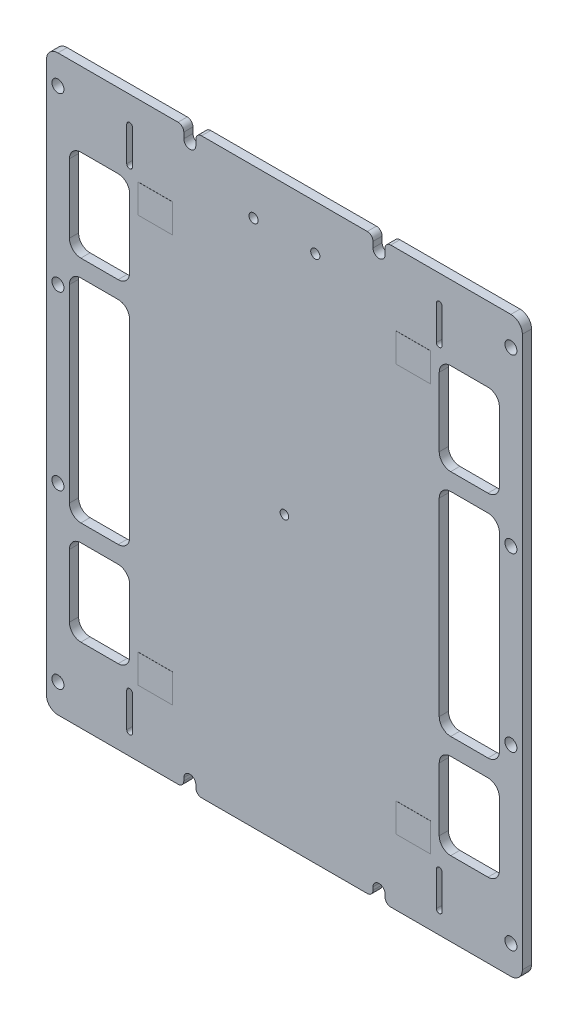
SolidWorks part; units mm, degrees
material "FR4_stuffedProtoboard"
ref_plane "Front Plane" through (0, 0, 0) normal (0, 0, 1) x (1, 0, 0)
ref_plane "Top Plane" through (0, 0, 0) normal (0, 1, 0) x (1, 0, 0)
ref_plane "Right Plane" through (0, 0, 0) normal (1, 0, 0) x (0, 0, -1)
sketch "Sketch1" plane through (0, 0, 0) normal (0, 0, 1) x (1, 0, 0)
  line L1 (-39.5, -50) -> (39.5, -50)
  line L2 (-41.5, -48) -> (-41.5, 48)
  line L3 (-39.5, 50) -> (39.5, 50)
  line L4 (41.5, -48) -> (41.5, 48)
  line L5 (-41.5, -50) -> (41.5, 50) construction
  line L6 (-41.5, 50) -> (41.5, -50) construction
  arc A0 (-39.5, -50) -> (-41.5, -48) centre (-39.5, -48) cw
  arc A1 (39.5, -50) -> (41.5, -48) centre (39.5, -48) ccw
  arc A2 (39.5, 50) -> (41.5, 48) centre (39.5, 48) cw
  arc A3 (-41.5, 48) -> (-39.5, 50) centre (-39.5, 48) cw
  point P0 (0, 0)
  dimension "D3" = 2
  dimension "D1" = 100
  dimension "D2" = 83
extrude "boardOutline" add sketch "Sketch1" along normal blind 1.6
sketch "Sketch2" plane through (0, 0, 1.6) normal (0, 0, 1) x (1, 0, 0)
  line L0 (39.5, 50) -> (-39.5, 50) construction
  line L1 (-41.5, 48) -> (-41.5, -48) construction
  line L2 (-5.385, 42.1) -> (5.385, 42.1) construction
  line L3 (-38, 44.2) -> (-38, 4.2) construction
  line L4 (0, 42.1) -> (0, 50) construction
  circle A0 centre (0, 0) radius 0.75
  circle A1 centre (-38, 44.2) radius 1.05 construction
  circle A2 centre (37.5, 44.2) radius 1.05 construction
  circle A3 centre (37.5, 4.2) radius 1.05 construction
  circle A4 centre (37.5, -35.8) radius 1.05 construction
  circle A5 centre (-38, 4.2) radius 1.05 construction
  circle A6 centre (-38, -35.8) radius 1.05 construction
  circle A7 centre (-5.385, 42.1) radius 0.8
  circle A8 centre (5.385, 42.1) radius 0.8
  dimension "D1" = 1.5
  dimension "D2" = 2.1
  dimension "D9" = 10.77
  dimension "D7" = 1.6
  dimension "D11" = 7.9
  dimension "D3" = 5.8
  dimension "D4" = 3.5
  dimension "D8" = 40
  dimension "D10" = 37.5
  dimension "D5" = 2
  dimension "D6" = 3
extrude "componentHoles" cut sketch "Sketch2" against normal through all
sketch "Sketch4" plane through (0, 0, 1.6) normal (0, 0, 1) x (1, 0, 0)
  line L0 (-27, 39.25) -> (-27, 45.25) construction
  line L1 (-27.5, 39.25) -> (-27.5, 45.25)
  line L2 (-26.5, 39.25) -> (-26.5, 45.25)
  line L3 (39.5, 50) -> (-39.5, 50) construction
  line L4 (-41.5, 48) -> (-41.5, -48) construction
  line L5 (27, 39.25) -> (27, 45.25) construction
  line L6 (26.5, 39.25) -> (26.5, 45.25)
  line L7 (27.5, 39.25) -> (27.5, 45.25)
  line L8 (27, -46.25) -> (27, -40.25) construction
  line L9 (26.5, -46.25) -> (26.5, -40.25)
  line L10 (27.5, -46.25) -> (27.5, -40.25)
  line L11 (-27, -46.25) -> (-27, -40.25) construction
  line L12 (-27.5, -46.25) -> (-27.5, -40.25)
  line L13 (-26.5, -46.25) -> (-26.5, -40.25)
  line L14 (-27, 39.25) -> (27, 39.25) construction
  line L15 (0, 39.25) -> (0, 50) construction
  arc A0 (-27.5, 39.25) -> (-26.5, 39.25) centre (-27, 39.25) ccw
  arc A1 (-26.5, 45.25) -> (-27.5, 45.25) centre (-27, 45.25) ccw
  arc A2 (26.5, 39.25) -> (27.5, 39.25) centre (27, 39.25) ccw
  arc A3 (27.5, 45.25) -> (26.5, 45.25) centre (27, 45.25) ccw
  arc A4 (26.5, -46.25) -> (27.5, -46.25) centre (27, -46.25) ccw
  arc A5 (27.5, -40.25) -> (26.5, -40.25) centre (27, -40.25) ccw
  arc A6 (-27.5, -46.25) -> (-26.5, -46.25) centre (-27, -46.25) ccw
  arc A7 (-26.5, -40.25) -> (-27.5, -40.25) centre (-27, -40.25) ccw
  point P2 (-27, 42.25)
  point P16 (27, 42.25)
  point P23 (27, -43.25)
  point P30 (-27, -43.25)
  dimension "D1" = 4.75
  dimension "D2" = 14
  dimension "D3" = 1
  dimension "D4" = 6
  dimension "D7" = 54
  dimension "D9" = 79.5
  dimension "D5" = 2
  dimension "D6" = 2
extrude "solarCellContactHoles" cut sketch "Sketch4" against normal blind 1.6
sketch "FrameLattice" plane through (0, 0, 0) normal (0, 0, 1) x (1, 0, 0)
  line L4 (-12.5, -19) -> (12.5, -19)
  line L5 (14.5, -17) -> (14.5, 16)
  line L6 (12.5, 18) -> (-12.5, 18)
  line L7 (-14.5, 16) -> (-14.5, -17)
  line L8 (-12.5, -19) -> (12.5, -19)
  line L9 (14.5, -17) -> (14.5, 16)
  line L10 (12.5, 18) -> (-12.5, 18)
  line L11 (-14.5, 16) -> (-14.5, -17)
  line L12 (-12.5, -92) -> (12.5, -92)
  line L13 (14.5, -90) -> (14.5, -69)
  line L14 (12.5, -67) -> (-12.5, -67)
  line L15 (-14.5, -69) -> (-14.5, -90)
  line L16 (-12.5, -92) -> (12.5, -92)
  line L17 (14.5, -90) -> (14.5, -69)
  line L18 (12.5, -67) -> (-12.5, -67)
  line L19 (-14.5, -69) -> (-14.5, -90)
  line L20 (-35.5, -132) -> (-19.5, -132)
  line L21 (-17.5, -130) -> (-17.5, -97)
  line L22 (-19.5, -95) -> (-35.5, -95)
  line L23 (-37.5, -97) -> (-37.5, -130)
  line L24 (-35.5, -132) -> (-19.5, -132)
  line L25 (-17.5, -130) -> (-17.5, -97)
  line L26 (-19.5, -95) -> (-35.5, -95)
  line L27 (-37.5, -97) -> (-37.5, -130)
  line L28 (19.5, -160) -> (35.5, -160)
  line L29 (37.5, -158) -> (37.5, -137)
  line L30 (35.5, -135) -> (19.5, -135)
  line L31 (17.5, -137) -> (17.5, -158)
  line L32 (19.5, -160) -> (35.5, -160)
  line L33 (37.5, -158) -> (37.5, -137)
  line L34 (35.5, -135) -> (19.5, -135)
  line L35 (17.5, -137) -> (17.5, -158)
  line L36 (19.5, -92) -> (35.5, -92)
  line L37 (37.5, -90) -> (37.5, -69)
  line L38 (35.5, -67) -> (19.5, -67)
  line L39 (17.5, -69) -> (17.5, -90)
  line L40 (19.5, -92) -> (35.5, -92)
  line L41 (37.5, -90) -> (37.5, -69)
  line L42 (35.5, -67) -> (19.5, -67)
  line L43 (17.5, -69) -> (17.5, -90)
  line L44 (-35.5, -92) -> (-19.5, -92)
  line L45 (-17.5, -90) -> (-17.5, -69)
  line L46 (-19.5, -67) -> (-35.5, -67)
  line L47 (-37.5, -69) -> (-37.5, -90)
  line L48 (-35.5, -92) -> (-19.5, -92)
  line L49 (-17.5, -90) -> (-17.5, -69)
  line L50 (-19.5, -67) -> (-35.5, -67)
  line L51 (-37.5, -69) -> (-37.5, -90)
  line L52 (19.5, -132) -> (35.5, -132)
  line L53 (37.5, -130) -> (37.5, -97)
  line L54 (35.5, -95) -> (19.5, -95)
  line L55 (17.5, -97) -> (17.5, -130)
  line L56 (19.5, -132) -> (35.5, -132)
  line L57 (37.5, -130) -> (37.5, -97)
  line L58 (35.5, -95) -> (19.5, -95)
  line L59 (17.5, -97) -> (17.5, -130)
  line L60 (-12.5, -160) -> (12.5, -160)
  line L61 (14.5, -158) -> (14.5, -137)
  line L62 (12.5, -135) -> (-12.5, -135)
  line L63 (-14.5, -137) -> (-14.5, -158)
  line L64 (-12.5, -160) -> (12.5, -160)
  line L65 (14.5, -158) -> (14.5, -137)
  line L66 (12.5, -135) -> (-12.5, -135)
  line L67 (-14.5, -137) -> (-14.5, -158)
  line L68 (-26.75, -62) -> (-26.75, -52)
  line L69 (-28.75, -50) -> (-35, -50)
  line L70 (-37, -52) -> (-37, -62)
  line L71 (-35, -64) -> (-28.75, -64)
  line L72 (-26.75, -62) -> (-26.75, -52)
  line L73 (-28.75, -50) -> (-35, -50)
  line L74 (-37, -52) -> (-37, -62)
  line L75 (-35, -64) -> (-28.75, -64)
  line L76 (-35.5, -160) -> (-19.5, -160)
  line L77 (-17.5, -158) -> (-17.5, -137)
  line L78 (-19.5, -135) -> (-35.5, -135)
  line L79 (-37.5, -137) -> (-37.5, -158)
  line L80 (-35.5, -160) -> (-19.5, -160)
  line L81 (-17.5, -158) -> (-17.5, -137)
  line L82 (-19.5, -135) -> (-35.5, -135)
  line L83 (-37.5, -137) -> (-37.5, -158)
  line L84 (-12.5, -132) -> (12.5, -132)
  line L85 (14.5, -130) -> (14.5, -97)
  line L86 (12.5, -95) -> (-12.5, -95)
  line L87 (-14.5, -97) -> (-14.5, -130)
  line L88 (-12.5, -132) -> (12.5, -132)
  line L89 (14.5, -130) -> (14.5, -97)
  line L90 (12.5, -95) -> (-12.5, -95)
  line L91 (-14.5, -97) -> (-14.5, -130)
  line L92 (-35.5, -19) -> (-19.5, -19)
  line L93 (-17.5, -17) -> (-17.5, 16)
  line L94 (-19.5, 18) -> (-35.5, 18)
  line L95 (-37.5, 16) -> (-37.5, -17)
  line L96 (-35.5, -19) -> (-19.5, -19)
  line L97 (-17.5, -17) -> (-17.5, 16)
  line L98 (-19.5, 18) -> (-35.5, 18)
  line L99 (-37.5, 16) -> (-37.5, -17)
  line L100 (19.5, -47) -> (35.5, -47)
  line L101 (37.5, -45) -> (37.5, -24)
  line L102 (35.5, -22) -> (19.5, -22)
  line L103 (17.5, -24) -> (17.5, -45)
  line L104 (19.5, -47) -> (35.5, -47)
  line L105 (37.5, -45) -> (37.5, -24)
  line L106 (35.5, -22) -> (19.5, -22)
  line L107 (17.5, -24) -> (17.5, -45)
  line L108 (-12.5, -47) -> (12.5, -47)
  line L109 (14.5, -45) -> (14.5, -24)
  line L110 (12.5, -22) -> (-12.5, -22)
  line L111 (-14.5, -24) -> (-14.5, -45)
  line L112 (-12.5, -47) -> (12.5, -47)
  line L113 (14.5, -45) -> (14.5, -24)
  line L114 (12.5, -22) -> (-12.5, -22)
  line L115 (-14.5, -24) -> (-14.5, -45)
  line L116 (-35.5, -47) -> (-19.5, -47)
  line L117 (-17.5, -45) -> (-17.5, -24)
  line L118 (-19.5, -22) -> (-35.5, -22)
  line L119 (-37.5, -24) -> (-37.5, -45)
  line L120 (-35.5, -47) -> (-19.5, -47)
  line L121 (-17.5, -45) -> (-17.5, -24)
  line L122 (-19.5, -22) -> (-35.5, -22)
  line L123 (-37.5, -24) -> (-37.5, -45)
  line L124 (19.5, -19) -> (35.5, -19)
  line L125 (37.5, -17) -> (37.5, 16)
  line L126 (35.5, 18) -> (19.5, 18)
  line L127 (17.5, 16) -> (17.5, -17)
  line L128 (19.5, -19) -> (35.5, -19)
  line L129 (37.5, -17) -> (37.5, 16)
  line L130 (35.5, 18) -> (19.5, 18)
  line L131 (17.5, 16) -> (17.5, -17)
  line L132 (-35.5, 21) -> (-19.5, 21)
  line L133 (-17.5, 23) -> (-17.5, 44)
  line L134 (-19.5, 46) -> (-35.5, 46)
  line L135 (-37.5, 44) -> (-37.5, 23)
  line L136 (-35.5, 21) -> (-19.5, 21)
  line L137 (-17.5, 23) -> (-17.5, 44)
  line L138 (-19.5, 46) -> (-35.5, 46)
  line L139 (-37.5, 44) -> (-37.5, 23)
  line L140 (-12.5, 21) -> (12.5, 21)
  line L141 (14.5, 23) -> (14.5, 44)
  line L142 (12.5, 46) -> (-12.5, 46)
  line L143 (-14.5, 44) -> (-14.5, 23)
  line L144 (-12.5, 21) -> (12.5, 21)
  line L145 (14.5, 23) -> (14.5, 44)
  line L146 (12.5, 46) -> (-12.5, 46)
  line L147 (-14.5, 44) -> (-14.5, 23)
  line L148 (19.5, 21) -> (35.5, 21)
  line L149 (37.5, 23) -> (37.5, 44)
  line L150 (35.5, 46) -> (19.5, 46)
  line L151 (17.5, 44) -> (17.5, 23)
  line L152 (19.5, 21) -> (35.5, 21)
  line L153 (37.5, 23) -> (37.5, 44)
  line L154 (35.5, 46) -> (19.5, 46)
  line L155 (17.5, 44) -> (17.5, 23)
  line L156 (-3.5, -62) -> (-3.5, -52)
  line L157 (-5.5, -50) -> (-13, -50)
  line L158 (-15, -52) -> (-15, -62)
  line L159 (-13, -64) -> (-5.5, -64)
  line L160 (-3.5, -62) -> (-3.5, -52)
  line L161 (-5.5, -50) -> (-13, -50)
  line L162 (-15, -52) -> (-15, -62)
  line L163 (-13, -64) -> (-5.5, -64)
  line L164 (28.75, -64) -> (35, -64)
  line L165 (37, -62) -> (37, -52)
  line L166 (35, -50) -> (28.75, -50)
  line L167 (26.75, -52) -> (26.75, -62)
  line L168 (28.75, -64) -> (35, -64)
  line L169 (37, -62) -> (37, -52)
  line L170 (35, -50) -> (28.75, -50)
  line L171 (26.75, -52) -> (26.75, -62)
  line L172 (5.5, -64) -> (13, -64)
  line L173 (15, -62) -> (15, -52)
  line L174 (13, -50) -> (5.5, -50)
  line L175 (3.5, -52) -> (3.5, -62)
  line L176 (5.5, -64) -> (13, -64)
  line L177 (15, -62) -> (15, -52)
  line L178 (13, -50) -> (5.5, -50)
  line L179 (3.5, -52) -> (3.5, -62)
  circle A2 centre (-16.5, 48) radius 0.8
  circle A3 centre (-16.5, 48) radius 0.8
  circle A4 centre (-16.5, -162) radius 0.8
  arc A5 (12.5, -19) -> (14.5, -17) centre (12.5, -17) ccw
  arc A6 (14.5, 16) -> (12.5, 18) centre (12.5, 16) ccw
  arc A7 (-12.5, 18) -> (-14.5, 16) centre (-12.5, 16) ccw
  arc A8 (-14.5, -17) -> (-12.5, -19) centre (-12.5, -17) ccw
  arc A9 (12.5, -19) -> (14.5, -17) centre (12.5, -17) ccw
  arc A10 (14.5, 16) -> (12.5, 18) centre (12.5, 16) ccw
  arc A11 (-12.5, 18) -> (-14.5, 16) centre (-12.5, 16) ccw
  arc A12 (-14.5, -17) -> (-12.5, -19) centre (-12.5, -17) ccw
  arc A13 (12.5, -92) -> (14.5, -90) centre (12.5, -90) ccw
  arc A14 (14.5, -69) -> (12.5, -67) centre (12.5, -69) ccw
  arc A15 (-12.5, -67) -> (-14.5, -69) centre (-12.5, -69) ccw
  arc A16 (-14.5, -90) -> (-12.5, -92) centre (-12.5, -90) ccw
  arc A17 (12.5, -92) -> (14.5, -90) centre (12.5, -90) ccw
  arc A18 (14.5, -69) -> (12.5, -67) centre (12.5, -69) ccw
  arc A19 (-12.5, -67) -> (-14.5, -69) centre (-12.5, -69) ccw
  arc A20 (-14.5, -90) -> (-12.5, -92) centre (-12.5, -90) ccw
  arc A21 (-19.5, -132) -> (-17.5, -130) centre (-19.5, -130) ccw
  arc A22 (-17.5, -97) -> (-19.5, -95) centre (-19.5, -97) ccw
  arc A23 (-35.5, -95) -> (-37.5, -97) centre (-35.5, -97) ccw
  arc A24 (-37.5, -130) -> (-35.5, -132) centre (-35.5, -130) ccw
  arc A25 (-19.5, -132) -> (-17.5, -130) centre (-19.5, -130) ccw
  arc A26 (-17.5, -97) -> (-19.5, -95) centre (-19.5, -97) ccw
  arc A27 (-35.5, -95) -> (-37.5, -97) centre (-35.5, -97) ccw
  arc A28 (-37.5, -130) -> (-35.5, -132) centre (-35.5, -130) ccw
  arc A29 (35.5, -160) -> (37.5, -158) centre (35.5, -158) ccw
  arc A30 (37.5, -137) -> (35.5, -135) centre (35.5, -137) ccw
  arc A31 (19.5, -135) -> (17.5, -137) centre (19.5, -137) ccw
  arc A32 (17.5, -158) -> (19.5, -160) centre (19.5, -158) ccw
  arc A33 (35.5, -160) -> (37.5, -158) centre (35.5, -158) ccw
  arc A34 (37.5, -137) -> (35.5, -135) centre (35.5, -137) ccw
  arc A35 (19.5, -135) -> (17.5, -137) centre (19.5, -137) ccw
  arc A36 (17.5, -158) -> (19.5, -160) centre (19.5, -158) ccw
  arc A37 (35.5, -92) -> (37.5, -90) centre (35.5, -90) ccw
  arc A38 (37.5, -69) -> (35.5, -67) centre (35.5, -69) ccw
  arc A39 (19.5, -67) -> (17.5, -69) centre (19.5, -69) ccw
  arc A40 (17.5, -90) -> (19.5, -92) centre (19.5, -90) ccw
  arc A41 (35.5, -92) -> (37.5, -90) centre (35.5, -90) ccw
  arc A42 (37.5, -69) -> (35.5, -67) centre (35.5, -69) ccw
  arc A43 (19.5, -67) -> (17.5, -69) centre (19.5, -69) ccw
  arc A44 (17.5, -90) -> (19.5, -92) centre (19.5, -90) ccw
  arc A45 (-19.5, -92) -> (-17.5, -90) centre (-19.5, -90) ccw
  arc A46 (-17.5, -69) -> (-19.5, -67) centre (-19.5, -69) ccw
  arc A47 (-35.5, -67) -> (-37.5, -69) centre (-35.5, -69) ccw
  arc A48 (-37.5, -90) -> (-35.5, -92) centre (-35.5, -90) ccw
  arc A49 (-19.5, -92) -> (-17.5, -90) centre (-19.5, -90) ccw
  arc A50 (-17.5, -69) -> (-19.5, -67) centre (-19.5, -69) ccw
  arc A51 (-35.5, -67) -> (-37.5, -69) centre (-35.5, -69) ccw
  arc A52 (-37.5, -90) -> (-35.5, -92) centre (-35.5, -90) ccw
  arc A53 (35.5, -132) -> (37.5, -130) centre (35.5, -130) ccw
  arc A54 (37.5, -97) -> (35.5, -95) centre (35.5, -97) ccw
  arc A55 (19.5, -95) -> (17.5, -97) centre (19.5, -97) ccw
  arc A56 (17.5, -130) -> (19.5, -132) centre (19.5, -130) ccw
  arc A57 (35.5, -132) -> (37.5, -130) centre (35.5, -130) ccw
  arc A58 (37.5, -97) -> (35.5, -95) centre (35.5, -97) ccw
  arc A59 (19.5, -95) -> (17.5, -97) centre (19.5, -97) ccw
  arc A60 (17.5, -130) -> (19.5, -132) centre (19.5, -130) ccw
  arc A61 (12.5, -160) -> (14.5, -158) centre (12.5, -158) ccw
  arc A62 (14.5, -137) -> (12.5, -135) centre (12.5, -137) ccw
  arc A63 (-12.5, -135) -> (-14.5, -137) centre (-12.5, -137) ccw
  arc A64 (-14.5, -158) -> (-12.5, -160) centre (-12.5, -158) ccw
  arc A65 (12.5, -160) -> (14.5, -158) centre (12.5, -158) ccw
  arc A66 (14.5, -137) -> (12.5, -135) centre (12.5, -137) ccw
  arc A67 (-12.5, -135) -> (-14.5, -137) centre (-12.5, -137) ccw
  arc A68 (-14.5, -158) -> (-12.5, -160) centre (-12.5, -158) ccw
  circle A69 centre (-16.5, -162) radius 0.8
  circle A70 centre (16.5, -162) radius 0.8
  circle A71 centre (16.5, -162) radius 0.8
  circle A72 centre (-16.5, -65.5) radius 0.8
  circle A73 centre (-16.5, -65.5) radius 0.8
  circle A74 centre (16.5, -65.5) radius 0.8
  circle A75 centre (16.5, -65.5) radius 0.8
  circle A76 centre (-39.5, -129) radius 0.8
  circle A77 centre (-39.5, -129) radius 0.8
  circle A78 centre (39.5, -159) radius 0.8
  circle A79 centre (39.5, -159) radius 0.8
  circle A80 centre (-39.5, -159) radius 0.8
  circle A81 centre (-39.5, -159) radius 0.8
  circle A82 centre (39.5, -129) radius 0.8
  circle A83 centre (39.5, -129) radius 0.8
  circle A84 centre (39.5, -99) radius 0.8
  circle A85 centre (39.5, -99) radius 0.8
  circle A86 centre (-39.5, -99) radius 0.8
  circle A87 centre (-39.5, -99) radius 0.8
  circle A88 centre (-39.5, -69) radius 0.8
  circle A89 centre (-39.5, -69) radius 0.8
  circle A90 centre (39.5, -69) radius 0.8
  circle A91 centre (39.5, -69) radius 0.8
  circle A92 centre (39.5, -15) radius 0.8
  circle A93 centre (39.5, -15) radius 0.8
  circle A94 centre (39.5, 15) radius 0.8
  arc A95 (-26.75, -52) -> (-28.75, -50) centre (-28.75, -52) ccw
  arc A96 (-35, -50) -> (-37, -52) centre (-35, -52) ccw
  arc A97 (-37, -62) -> (-35, -64) centre (-35, -62) ccw
  arc A98 (-28.75, -64) -> (-26.75, -62) centre (-28.75, -62) ccw
  arc A99 (-26.75, -52) -> (-28.75, -50) centre (-28.75, -52) ccw
  arc A100 (-35, -50) -> (-37, -52) centre (-35, -52) ccw
  arc A101 (-37, -62) -> (-35, -64) centre (-35, -62) ccw
  arc A102 (-28.75, -64) -> (-26.75, -62) centre (-28.75, -62) ccw
  arc A103 (-19.5, -160) -> (-17.5, -158) centre (-19.5, -158) ccw
  arc A104 (-17.5, -137) -> (-19.5, -135) centre (-19.5, -137) ccw
  arc A105 (-35.5, -135) -> (-37.5, -137) centre (-35.5, -137) ccw
  arc A106 (-37.5, -158) -> (-35.5, -160) centre (-35.5, -158) ccw
  arc A107 (-19.5, -160) -> (-17.5, -158) centre (-19.5, -158) ccw
  arc A108 (-17.5, -137) -> (-19.5, -135) centre (-19.5, -137) ccw
  arc A109 (-35.5, -135) -> (-37.5, -137) centre (-35.5, -137) ccw
  arc A110 (-37.5, -158) -> (-35.5, -160) centre (-35.5, -158) ccw
  arc A111 (12.5, -132) -> (14.5, -130) centre (12.5, -130) ccw
  arc A112 (14.5, -97) -> (12.5, -95) centre (12.5, -97) ccw
  arc A113 (-12.5, -95) -> (-14.5, -97) centre (-12.5, -97) ccw
  arc A114 (-14.5, -130) -> (-12.5, -132) centre (-12.5, -130) ccw
  arc A115 (12.5, -132) -> (14.5, -130) centre (12.5, -130) ccw
  arc A116 (14.5, -97) -> (12.5, -95) centre (12.5, -97) ccw
  arc A117 (-12.5, -95) -> (-14.5, -97) centre (-12.5, -97) ccw
  arc A118 (-14.5, -130) -> (-12.5, -132) centre (-12.5, -130) ccw
  arc A119 (-19.5, -19) -> (-17.5, -17) centre (-19.5, -17) ccw
  arc A120 (-17.5, 16) -> (-19.5, 18) centre (-19.5, 16) ccw
  arc A121 (-35.5, 18) -> (-37.5, 16) centre (-35.5, 16) ccw
  arc A122 (-37.5, -17) -> (-35.5, -19) centre (-35.5, -17) ccw
  arc A123 (-19.5, -19) -> (-17.5, -17) centre (-19.5, -17) ccw
  arc A124 (-17.5, 16) -> (-19.5, 18) centre (-19.5, 16) ccw
  arc A125 (-35.5, 18) -> (-37.5, 16) centre (-35.5, 16) ccw
  arc A126 (-37.5, -17) -> (-35.5, -19) centre (-35.5, -17) ccw
  arc A127 (35.5, -47) -> (37.5, -45) centre (35.5, -45) ccw
  arc A128 (37.5, -24) -> (35.5, -22) centre (35.5, -24) ccw
  arc A129 (19.5, -22) -> (17.5, -24) centre (19.5, -24) ccw
  arc A130 (17.5, -45) -> (19.5, -47) centre (19.5, -45) ccw
  arc A131 (35.5, -47) -> (37.5, -45) centre (35.5, -45) ccw
  arc A132 (37.5, -24) -> (35.5, -22) centre (35.5, -24) ccw
  arc A133 (19.5, -22) -> (17.5, -24) centre (19.5, -24) ccw
  arc A134 (17.5, -45) -> (19.5, -47) centre (19.5, -45) ccw
  arc A135 (12.5, -47) -> (14.5, -45) centre (12.5, -45) ccw
  arc A136 (14.5, -24) -> (12.5, -22) centre (12.5, -24) ccw
  arc A137 (-12.5, -22) -> (-14.5, -24) centre (-12.5, -24) ccw
  arc A138 (-14.5, -45) -> (-12.5, -47) centre (-12.5, -45) ccw
  arc A139 (12.5, -47) -> (14.5, -45) centre (12.5, -45) ccw
  arc A140 (14.5, -24) -> (12.5, -22) centre (12.5, -24) ccw
  arc A141 (-12.5, -22) -> (-14.5, -24) centre (-12.5, -24) ccw
  arc A142 (-14.5, -45) -> (-12.5, -47) centre (-12.5, -45) ccw
  arc A143 (-19.5, -47) -> (-17.5, -45) centre (-19.5, -45) ccw
  arc A144 (-17.5, -24) -> (-19.5, -22) centre (-19.5, -24) ccw
  arc A145 (-35.5, -22) -> (-37.5, -24) centre (-35.5, -24) ccw
  arc A146 (-37.5, -45) -> (-35.5, -47) centre (-35.5, -45) ccw
  arc A147 (-19.5, -47) -> (-17.5, -45) centre (-19.5, -45) ccw
  arc A148 (-17.5, -24) -> (-19.5, -22) centre (-19.5, -24) ccw
  arc A149 (-35.5, -22) -> (-37.5, -24) centre (-35.5, -24) ccw
  arc A150 (-37.5, -45) -> (-35.5, -47) centre (-35.5, -45) ccw
  arc A151 (35.5, -19) -> (37.5, -17) centre (35.5, -17) ccw
  arc A152 (37.5, 16) -> (35.5, 18) centre (35.5, 16) ccw
  arc A153 (19.5, 18) -> (17.5, 16) centre (19.5, 16) ccw
  arc A154 (17.5, -17) -> (19.5, -19) centre (19.5, -17) ccw
  arc A155 (35.5, -19) -> (37.5, -17) centre (35.5, -17) ccw
  arc A156 (37.5, 16) -> (35.5, 18) centre (35.5, 16) ccw
  arc A157 (19.5, 18) -> (17.5, 16) centre (19.5, 16) ccw
  arc A158 (17.5, -17) -> (19.5, -19) centre (19.5, -17) ccw
  arc A159 (-19.5, 21) -> (-17.5, 23) centre (-19.5, 23) ccw
  arc A160 (-17.5, 44) -> (-19.5, 46) centre (-19.5, 44) ccw
  arc A161 (-35.5, 46) -> (-37.5, 44) centre (-35.5, 44) ccw
  arc A162 (-37.5, 23) -> (-35.5, 21) centre (-35.5, 23) ccw
  arc A163 (-19.5, 21) -> (-17.5, 23) centre (-19.5, 23) ccw
  arc A164 (-17.5, 44) -> (-19.5, 46) centre (-19.5, 44) ccw
  arc A165 (-35.5, 46) -> (-37.5, 44) centre (-35.5, 44) ccw
  arc A166 (-37.5, 23) -> (-35.5, 21) centre (-35.5, 23) ccw
  arc A167 (12.5, 21) -> (14.5, 23) centre (12.5, 23) ccw
  arc A168 (14.5, 44) -> (12.5, 46) centre (12.5, 44) ccw
  arc A169 (-12.5, 46) -> (-14.5, 44) centre (-12.5, 44) ccw
  arc A170 (-14.5, 23) -> (-12.5, 21) centre (-12.5, 23) ccw
  arc A171 (12.5, 21) -> (14.5, 23) centre (12.5, 23) ccw
  arc A172 (14.5, 44) -> (12.5, 46) centre (12.5, 44) ccw
  arc A173 (-12.5, 46) -> (-14.5, 44) centre (-12.5, 44) ccw
  arc A174 (-14.5, 23) -> (-12.5, 21) centre (-12.5, 23) ccw
  arc A175 (35.5, 21) -> (37.5, 23) centre (35.5, 23) ccw
  arc A176 (37.5, 44) -> (35.5, 46) centre (35.5, 44) ccw
  arc A177 (19.5, 46) -> (17.5, 44) centre (19.5, 44) ccw
  arc A178 (17.5, 23) -> (19.5, 21) centre (19.5, 23) ccw
  arc A179 (35.5, 21) -> (37.5, 23) centre (35.5, 23) ccw
  arc A180 (37.5, 44) -> (35.5, 46) centre (35.5, 44) ccw
  arc A181 (19.5, 46) -> (17.5, 44) centre (19.5, 44) ccw
  arc A182 (17.5, 23) -> (19.5, 21) centre (19.5, 23) ccw
  circle A183 centre (39.5, 15) radius 0.8
  circle A184 centre (-39.5, 45) radius 0.8
  circle A185 centre (-39.5, 45) radius 0.8
  circle A186 centre (39.5, 45) radius 0.8
  circle A187 centre (39.5, 45) radius 0.8
  circle A188 centre (-39.5, 15) radius 0.8
  circle A189 centre (-39.5, 15) radius 0.8
  circle A190 centre (16.5, -48.5) radius 0.8
  circle A191 centre (16.5, -48.5) radius 0.8
  circle A192 centre (-16.5, -48.5) radius 0.8
  circle A193 centre (-16.5, -48.5) radius 0.8
  circle A194 centre (16.5, 48) radius 0.8
  circle A195 centre (16.5, 48) radius 0.8
  circle A196 centre (-39.5, -15) radius 0.8
  circle A197 centre (-39.5, -15) radius 0.8
  circle A198 centre (-22, -61) radius 2.75
  circle A199 centre (-22, -61) radius 2.75
  circle A200 centre (-22, -53) radius 2.75
  circle A201 centre (-22, -53) radius 2.75
  circle A202 centre (22, -53) radius 2.75
  circle A203 centre (22, -53) radius 2.75
  circle A204 centre (22, -61) radius 2.75
  arc A205 (-3.5, -52) -> (-5.5, -50) centre (-5.5, -52) ccw
  arc A206 (-13, -50) -> (-15, -52) centre (-13, -52) ccw
  arc A207 (-15, -62) -> (-13, -64) centre (-13, -62) ccw
  arc A208 (-5.5, -64) -> (-3.5, -62) centre (-5.5, -62) ccw
  arc A209 (-3.5, -52) -> (-5.5, -50) centre (-5.5, -52) ccw
  arc A210 (-13, -50) -> (-15, -52) centre (-13, -52) ccw
  arc A211 (-15, -62) -> (-13, -64) centre (-13, -62) ccw
  arc A212 (-5.5, -64) -> (-3.5, -62) centre (-5.5, -62) ccw
  circle A213 centre (22, -61) radius 2.75
  circle A214 centre (0, -57) radius 2.75
  circle A215 centre (0, -57) radius 2.75
  circle A216 centre (39.5, -45) radius 0.8
  circle A217 centre (39.5, -45) radius 0.8
  circle A218 centre (-39.5, -45) radius 0.8
  arc A219 (35, -64) -> (37, -62) centre (35, -62) ccw
  arc A220 (37, -52) -> (35, -50) centre (35, -52) ccw
  arc A221 (28.75, -50) -> (26.75, -52) centre (28.75, -52) ccw
  arc A222 (26.75, -62) -> (28.75, -64) centre (28.75, -62) ccw
  arc A223 (35, -64) -> (37, -62) centre (35, -62) ccw
  arc A224 (37, -52) -> (35, -50) centre (35, -52) ccw
  arc A225 (28.75, -50) -> (26.75, -52) centre (28.75, -52) ccw
  arc A226 (26.75, -62) -> (28.75, -64) centre (28.75, -62) ccw
  arc A227 (13, -64) -> (15, -62) centre (13, -62) ccw
  arc A228 (15, -52) -> (13, -50) centre (13, -52) ccw
  arc A229 (5.5, -50) -> (3.5, -52) centre (5.5, -52) ccw
  arc A230 (3.5, -62) -> (5.5, -64) centre (5.5, -62) ccw
  arc A231 (13, -64) -> (15, -62) centre (13, -62) ccw
  arc A232 (15, -52) -> (13, -50) centre (13, -52) ccw
  arc A233 (5.5, -50) -> (3.5, -52) centre (5.5, -52) ccw
  arc A234 (3.5, -62) -> (5.5, -64) centre (5.5, -62) ccw
  circle A235 centre (-39.5, -45) radius 0.8
  dimension "D1" = 0
  dimension "D2" = 0
  dimension "D3" = 0
  dimension "D4" = 0
  dimension "D5" = 0
  dimension "D6" = 0
  dimension "D7" = 0
  dimension "D8" = 0
  dimension "D9" = 0
  dimension "D10" = 0
  dimension "D11" = 0
  dimension "D12" = 0
  dimension "D13" = 0
  dimension "D14" = 0
  dimension "D15" = 0
  dimension "D16" = 0
  dimension "D17" = 0
  dimension "D18" = 0
  dimension "D19" = 0
  dimension "D20" = 0
  dimension "D21" = 0
  dimension "D22" = 0
  dimension "D23" = 0
  dimension "D24" = 0
  dimension "D25" = 0
  dimension "D26" = 0
  dimension "D27" = 0
  dimension "D28" = 0
  dimension "D29" = 0
  dimension "D30" = 0
  dimension "D31" = 0
  dimension "D32" = 0
  dimension "D33" = 0
  dimension "D34" = 0
  dimension "D35" = 0
  dimension "D36" = 0
  dimension "D37" = 0
  dimension "D38" = 0
  dimension "D39" = 0
  dimension "D40" = 0
  dimension "D41" = 0
  dimension "D42" = 0
  dimension "D43" = 0
  dimension "D44" = 0
  dimension "D45" = 0
  dimension "D46" = 0
  dimension "D47" = 0
  dimension "D48" = 0
  dimension "D49" = 0
  dimension "D50" = 0
  dimension "D51" = 0
sketch "Sketch3" plane through (0, 0, 1.6) normal (0, 0, 1) x (1, 0, 0)
  line L0 (-35.5, -19) -> (-19.5, -19) construction
  line L1 (-35.5, 37) -> (-29, 37)
  line L2 (-37.5, 35) -> (-37.5, 23)
  line L3 (-35.5, 21) -> (-29, 21)
  line L4 (-27, 35) -> (-27, 23)
  line L6 (-29, -22) -> (-35.5, -22)
  line L7 (-37.5, 16) -> (-37.5, -17) construction
  line L8 (-19.5, -22) -> (-35.5, -22) construction
  line L9 (0, 50) -> (0, -50) construction
  line L10 (39.5, 50) -> (-39.5, 50) construction
  line L11 (-39.5, -50) -> (39.5, -50) construction
  line L12 (-27, -24) -> (-27, -35)
  line L13 (-29, -37) -> (-35.5, -37)
  line L14 (-37.5, -24) -> (-37.5, -35)
  line L15 (-19.5, 18) -> (-35.5, 18) construction
  line L16 (-35.5, 21) -> (-19.5, 21) construction
  line L19 (-29, -19) -> (-35.5, -19)
  line L25 (-27, -17) -> (-27, 16)
  line L26 (-29, 18) -> (-35.5, 18)
  line L27 (-37.5, -17) -> (-37.5, 16)
  arc A0 (-37.5, 23) -> (-35.5, 21) centre (-35.5, 23) ccw
  arc A1 (-29, 21) -> (-27, 23) centre (-29, 23) ccw
  arc A2 (-29, 37) -> (-27, 35) centre (-29, 35) cw
  arc A3 (-35.5, 37) -> (-37.5, 35) centre (-35.5, 35) ccw
  arc A4 (-29, -19) -> (-27, -17) centre (-29, -17) ccw
  arc A5 (-27, -35) -> (-29, -37) centre (-29, -35) cw
  arc A6 (-35.5, -37) -> (-37.5, -35) centre (-35.5, -35) cw
  arc A7 (-35.5, -22) -> (-37.5, -24) centre (-35.5, -24) ccw
  arc A8 (-29, -22) -> (-27, -24) centre (-29, -24) cw
  arc A9 (-37.5, 23) -> (-35.5, 21) centre (-35.5, 23) ccw construction
  arc A17 (-35.5, -19) -> (-37.5, -17) centre (-35.5, -17) cw
  arc A18 (-35.5, 18) -> (-37.5, 16) centre (-35.5, 16) ccw
  arc A19 (-27, 16) -> (-29, 18) centre (-29, 16) ccw
  point P12 (-27, 21)
  point P15 (-27, 37)
  point P18 (-37.5, 37)
  dimension "D10" = 13
  dimension "D1" = 10.5
  dimension "D3" = 13
extrude "windows_1side" cut sketch "Sketch3" against normal through all
sketch "Sketch5" plane through (0, 0, 1.6) normal (0, 0, 1) x (1, 0, 0)
  line L0 (-41.5, 48) -> (-41.5, -48) construction
  line L1 (-25.5, 37.5) -> (-19.5, 37.5)
  line L2 (-25.5, 37.5) -> (-25.5, 32.5)
  line L3 (-25.5, 32.5) -> (-19.5, 32.5)
  line L4 (-19.5, 37.5) -> (-19.5, 32.5)
  line L5 (0, 37.5) -> (0, 50) construction
  line L6 (19.5, 37.5) -> (19.5, 32.5)
  line L7 (25.5, 37.5) -> (25.5, 32.5)
  line L8 (19.5, 32.5) -> (25.5, 32.5)
  line L9 (19.5, 37.5) -> (25.5, 37.5)
  line L10 (19.5, -33.5) -> (19.5, -38.5)
  line L11 (25.5, -33.5) -> (25.5, -38.5)
  line L12 (19.5, -38.5) -> (25.5, -38.5)
  line L13 (19.5, -33.5) -> (25.5, -33.5)
  line L14 (-25.5, -33.5) -> (-25.5, -38.5)
  line L15 (-19.5, -33.5) -> (-19.5, -38.5)
  line L16 (-25.5, -38.5) -> (-19.5, -38.5)
  line L17 (-25.5, -33.5) -> (-19.5, -33.5)
  line L18 (-19.5, 37.5) -> (19.5, 37.5) construction
  line L19 (-25.5, 37.5) -> (-25.5, -33.5) construction
  line L20 (39.5, 50) -> (-39.5, 50) construction
  arc A0 (-27.5, 39.25) -> (-26.5, 39.25) centre (-27, 39.25) ccw construction
  dimension "D1" = 5
  dimension "D2" = 6
  dimension "D3" = 16
  dimension "D4" = 1.75
  dimension "D7" = 45
  dimension "D8" = 71
  dimension "D5" = 2
  dimension "D6" = 2
extrude "contactPads" add sketch "Sketch5" along normal blind 0.02
hole_wizard "M2 Clearance Hole1" positions "Sketch6" profile "Sketch7" hole size "M2" standard "ANSI Metric" end condition through all
sketch "Sketch6" plane through (0, 0, 0) normal (0, 0, -1) x (-1, 0, 0)
  line L5 (39.5, -50) -> (39.5, -45) construction
  line L6 (39.5, -50) -> (-39.5, -50) construction
  line L7 (39.5, -45) -> (39.5, -15) construction
  line L8 (39.5, -15) -> (39.5, 15) construction
  line L9 (39.5, 15) -> (39.5, 45) construction
  line L10 (39.5, 45) -> (39.5, 50) construction
  line L11 (-39.5, 50) -> (39.5, 50) construction
  line L15 (37.5, -27.0602) -> (41.5, -27.0602) construction
  line L16 (37.5, -24) -> (37.5, -35) construction
  line L17 (41.5, 48) -> (41.5, -48) construction
  point P0 (39.5, 45)
  point P27 (39.5, -15)
  point P36 (39.5, -45)
  point P38 (39.5, 15)
  point P73 (39.5, -27.0602)
  dimension "D2" = 5
sketch "Sketch7" plane through (-39.5, 45, 0) normal (1, 0, 0) x (0, 1, 0)
  line L0 (0, 0) -> (0, 1.62)
  line L1 (0, 1.62) -> (1.05, 1.62)
  line L2 (1.05, 1.62) -> (1.05, 0)
  line L5 (1.05, 0) -> (0, 0)
  line L11 (0, -6.35) -> (0, 107.95) construction
  dimension "Thru Hole Dia." = 2.1
  dimension "Thru Hole Depth" = 1.62
sketch "Sketch10" plane through (0, 0, 0) normal (0, 0, -1) x (-1, 0, 0)
  line L0 (16.5, 48) -> (16.5, 55.0732) construction
  line L1 (15.45, 48) -> (15.45, 55.0732)
  line L2 (17.55, 48) -> (17.55, 55.0732)
  line L3 (16.5, -48.5) -> (16.5, -55.5732) construction
  line L4 (17.55, -48.5) -> (17.55, -55.5732)
  line L5 (15.45, -48.5) -> (15.45, -55.5732)
  line L6 (41.5, 48) -> (41.5, -48) construction
  line L8 (39.5, -50) -> (-39.5, -50) construction
  line L9 (-39.5, 50) -> (39.5, 50) construction
  arc A0 (15.45, 48) -> (17.55, 48) centre (16.5, 48) ccw
  arc A1 (17.55, 55.0732) -> (15.45, 55.0732) centre (16.5, 55.0732) ccw
  arc A2 (17.55, -48.5) -> (15.45, -48.5) centre (16.5, -48.5) ccw
  arc A3 (15.45, -55.5732) -> (17.55, -55.5732) centre (16.5, -55.5732) ccw
  point P2 (16.5, 51.5366)
  point P7 (16.5, -52.0366)
  dimension "D1" = 1.05
  dimension "D2" = 25
  dimension "D3" = 2
  dimension "D4" = 1.5
extrude "Cut-Extrude1" cut sketch "Sketch10" against normal through all both and the other way through all
fillet "Fillet3" radius 1 4 edges at (-17.55, 50, 0.8) (-15.45, 50, 0.8) (-15.45, -50, 0.8) (-17.55, -50, 0.8)
mirror "Mirror1" about plane through (0, 0, 0) normal (1, 0, 0) of "Cut-Extrude1", "Fillet3", "windows_1side", "M2 Clearance Hole1"
